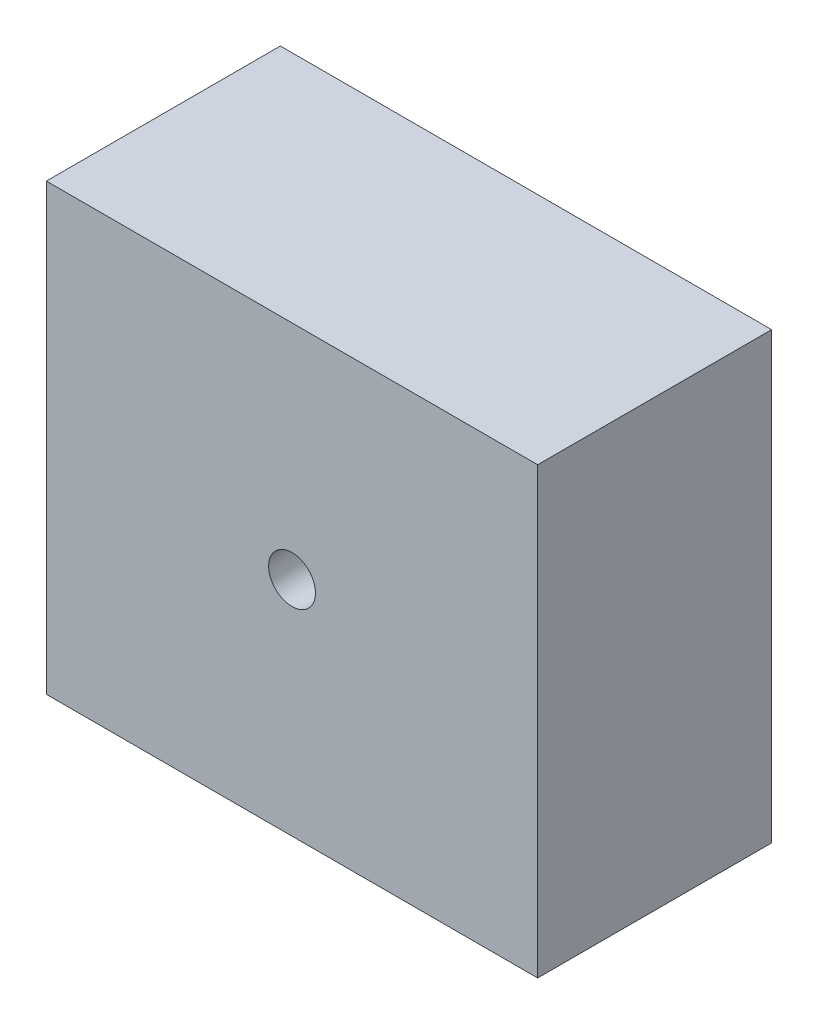
SolidWorks part; units mm, degrees
ref_plane "Front Plane" through (0, 0, 0) normal (0, 0, 1) x (1, 0, 0)
ref_plane "Top Plane" through (0, 0, 0) normal (0, 1, 0) x (1, 0, 0)
ref_plane "Right Plane" through (0, 0, 0) normal (1, 0, 0) x (0, 0, -1)
sketch "Sketch1" plane through (0, 0, 0) normal (0, 0, 1) x (1, 0, 0)
  line L1 (-10.5, -9.5) -> (10.5, -9.5)
  line L2 (-10.5, -9.5) -> (-10.5, 9.5)
  line L3 (-10.5, 9.5) -> (10.5, 9.5)
  line L4 (10.5, -9.5) -> (10.5, 9.5)
  line L5 (-10.5, -9.5) -> (10.5, 9.5) construction
  line L6 (-10.5, 9.5) -> (10.5, -9.5) construction
  point P0 (0, 0)
  dimension "D1" = 21
  dimension "D2" = 19
extrude "Boss-Extrude2" add sketch "Sketch1" along normal blind 10
sketch "Sketch3" plane through (0, 0, 0) normal (0, 0, -1) x (-1, 0, 0)
  line L1 (8.1, -7.1) -> (-8.1, -7.1)
  line L2 (8.1, -7.1) -> (8.1, 7.1)
  line L3 (8.1, 7.1) -> (-8.1, 7.1)
  line L4 (-8.1, -7.1) -> (-8.1, 7.1)
  line L5 (8.1, -7.1) -> (-8.1, 7.1) construction
  line L6 (8.1, 7.1) -> (-8.1, -7.1) construction
  point P0 (0, 0)
  dimension "D1" = 16.2
  dimension "D2" = 14.2
extrude "Cut-Extrude1" cut sketch "Sketch3" against normal blind 2.0193
sketch "Sketch4" plane through (0, 0, 2.0193) normal (0, 0, -1) x (-1, 0, 0)
  circle A0 centre (0, 0) radius 1
  dimension "D1" = 2
extrude "Cut-Extrude2" cut sketch "Sketch4" against normal blind 8
